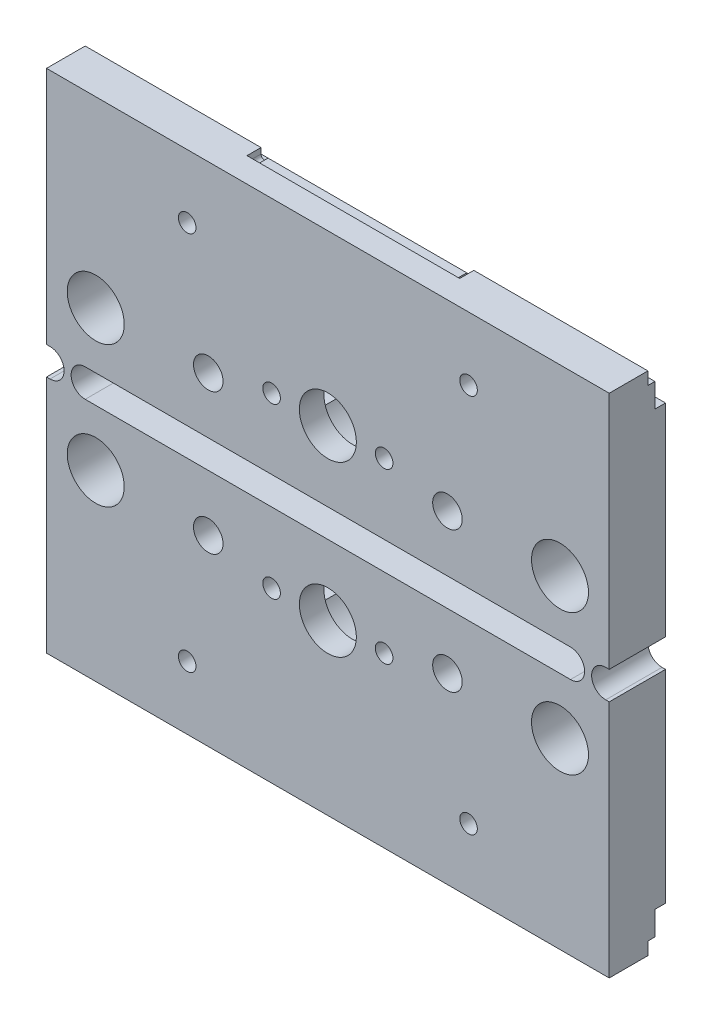
SolidWorks part; units mm, degrees
ref_plane "前视基准面" through (0, 0, 0) normal (0, 0, 1) x (1, 0, 0)
ref_plane "上视基准面" through (0, 0, 0) normal (0, 1, 0) x (1, 0, 0)
ref_plane "右视基准面" through (0, 0, 0) normal (1, 0, 0) x (0, 0, -1)
sketch "前视图草图" plane through (0, 0, 0) normal (0, 0, 1) x (1, 0, 0)
  line L0 (0, 0) -> (8.5179, 0) construction
  line L1 (0, 0) -> (0, 5.4227) construction
sketch "草图2" plane through (0, 0, 0) normal (0, 0, 1) x (1, 0, 0)
  line L0 (0, 0) -> (80, 0)
  line L1 (-200000, 0) -> (200008.5179, 0) construction
  line L2 (80, 0) -> (80, 34)
  line L3 (80, 34) -> (0, 34)
  line L4 (0, -200000) -> (0, 200005.4227) construction
  line L5 (0, 34) -> (0, 0)
  circle A0 centre (7, 8) radius 4.05
  circle A1 centre (40, 10) radius 4.05
  circle A2 centre (73, 8) radius 4.05
  dimension "D3" = 8
  dimension "D5" = 10
  dimension "D9" = 8.1
  dimension "D10" = 8.1
  dimension "D11" = 8.1
  dimension "D1" = 34
  dimension "D2" = 80
  dimension "D4" = 7
  dimension "D6" = 7
  dimension "D7" = 8
  dimension "D8" = 40
extrude "凸台-拉伸1" add sketch "草图2" along normal blind 8
sketch "草图3" plane through (0, 0, 8) normal (0, 0, 1) x (1, 0, 0)
  line L0 (16.088, 8) -> (31.4805, 8) construction
  line L1 (7, 8) -> (7, 16.8386) construction
  line L2 (73, 8) -> (73, 16.5917) construction
  line L4 (-200000, 0) -> (200008.5179, 0) construction
  circle A2 centre (23, 8) radius 2.55
  circle A3 centre (57, 8) radius 2.55
  dimension "D4" = 5.1
  dimension "D5" = 5.1
  dimension "D1" = 8
  dimension "D2" = 16
  dimension "D3" = 16
sketch "草图4" plane through (80, 0, 0) normal (1, 0, 0) x (0, 0, -1)
  line L1 (0, -200000) -> (0, 200005.4227) construction
  line L2 (-1.5, 32.2) -> (-2.5, 32.2)
  line L3 (-2.5, 32.2) -> (-2.5, 34)
  line L4 (-8, 34) -> (0, 34) construction
  line L5 (-2.5, 34) -> (0, 34)
  line L6 (-1.5, 32.2) -> (-1.5, 28.8)
  line L7 (-1.5, 28.8) -> (0, 28.8)
  line L8 (0, 28.8) -> (0, 34)
  dimension "D1" = 3.4
  dimension "D2" = 2.5
  dimension "D3" = 1.5
  dimension "D4" = 1.8
extrude "切除-拉伸2" cut sketch "草图4" against normal through all
sketch "草图5" plane through (0, 0, 8) normal (0, 0, 1) x (1, 0, 0)
  line L0 (40, 10) -> (56.5376, 10) construction
  circle A0 centre (40, 10) radius 8 construction
  circle A1 centre (48, 10) radius 1.55
  circle A2 centre (32, 10) radius 1.55
  dimension "D1" = 3.1
  dimension "D2" = 3.1
  dimension "D3" = 16
sketch "草图8" plane through (0, 0, 0) normal (0, 0, -1) x (-1, 0, 0)
  line L0 (-40, 10) -> (-57.3165, 10) construction
  line L1 (-40, 20) -> (-40, 35.6562) construction
  line L2 (-30.5, 12.85) -> (-49.5, 12.85)
  line L3 (-49.5, 7.15) -> (-30.5, 7.15)
  line L4 (200000, 0) -> (-200008.5179, 0) construction
  arc A0 (-30.5, 7.15) -> (-30.5, 12.85) centre (-30.5, 10) ccw
  arc A1 (-49.5, 12.85) -> (-49.5, 7.15) centre (-49.5, 10) ccw
  dimension "D1" = 5.7
  dimension "D2" = 9.5
  dimension "D3" = 9.5
  dimension "D4" = 10
extrude "切除-拉伸12" cut sketch "草图8" against normal blind 4.5
sketch "草图20" plane through (0, 0, 0) normal (0, 0, -1) x (-1, 0, 0)
  circle A0 centre (-40, 10) radius 6.25
  dimension "D1" = 12.5
extrude "切除-拉伸13" cut sketch "草图20" against normal blind 4.5
sketch "草图19" plane through (0, 0, 2.5) normal (0, 0, -1) x (-1, 0, 0)
  line L0 (0, 34) -> (-80, 34) construction
  line L1 (-25, 34) -> (-55.2479, 34)
  line L2 (-25, 34) -> (-25, 33.2)
  line L3 (-26, 33.2) -> (-54.2479, 33.2)
  line L4 (-55.2479, 34) -> (-55.2479, 33.2)
  line L5 (0, -200000) -> (0, 200005.4227) construction
  line L7 (0, 32.2) -> (-80, 32.2) construction
  line L8 (-56.3335, 32.7) -> (-52.9089, 32.7) construction
  line L9 (-55.2479, 1028.5823) -> (-55.2479, 33.2) construction
  line L10 (-25, 1028.5823) -> (-25, 32.7) construction
  line L11 (-55.2479, 32.7) -> (-55.2479, -973.3) construction
  line L12 (-25, 32.7) -> (-25, -973.3) construction
  arc A3 (-55.2479, 33.2) -> (-54.2479, 33.2) centre (-54.7479, 33.2) ccw
  arc A6 (-26, 33.2) -> (-25, 33.2) centre (-25.5, 33.2) ccw
  dimension "D3" = 1
  dimension "D4" = 1
  dimension "D2" = 0.8
  dimension "D1" = 0.5
  dimension "D9" = 25
extrude "切除-拉伸11" cut sketch "草图19" against normal blind 2
sketch "草图27" plane through (0, 0, 0) normal (0, 0, -1) x (-1, 0, 0)
  line L0 (-99.5618, 25) -> (-88.3386, 25) construction
  line L1 (-55.2479, 34) -> (-80, 34) construction
  line L2 (-60, 38.1181) -> (-60, 18.9205) construction
  line L3 (-20, 37.4289) -> (-20, 18.7236) construction
  line L4 (-80, 0) -> (-80, 28.8) construction
  line L5 (0, -200000) -> (0, 200005.4227) construction
  circle A0 centre (-60, 25) radius 1.55
  circle A1 centre (-20, 25) radius 1.55
  dimension "D4" = 3.1
  dimension "D5" = 3.1
  dimension "D1" = 9
  dimension "D2" = 20
  dimension "D3" = 20
hole_wizard "M5 螺纹孔1" positions "3D草图1" profile "草图25" tap size "M5" standard "GB" end condition through all
sketch3d "3D草图1"
  point P0 (57, 8, 8)
  point P3 (23, 8, 8)
sketch "草图25" plane through (57, 8, 8) normal (1, 0, 0) x (0, -1, 0)
  line L0 (0, 0) -> (0, 8)
  line L1 (0, 8) -> (2.1, 8)
  line L2 (2.1, 8) -> (2.1, 0)
  line L5 (2.1, 0) -> (0, 0)
  line L11 (0, -6.35) -> (0, 107.95) construction
  dimension "通孔螺纹孔钻头直径" = 4.2
  dimension "通孔螺纹孔钻头深度" = 8
cosmetic thread "孔螺蚊线1" parameters "D2"=5
cosmetic thread "孔螺蚊线2" parameters "D2"=5
hole_wizard "M3 螺纹孔1" positions "3D草图2" profile "草图26" tap size "M3" standard "GB" end condition through all
sketch3d "3D草图2"
  point P0 (48, 10, 8)
  point P3 (32, 10, 8)
sketch "草图26" plane through (48, 10, 8) normal (1, 0, 0) x (0, -1, 0)
  line L0 (0, 0) -> (0, 8)
  line L1 (0, 8) -> (1.25, 8)
  line L2 (1.25, 8) -> (1.25, 0)
  line L5 (1.25, 0) -> (0, 0)
  line L11 (0, -6.35) -> (0, 107.95) construction
  dimension "通孔螺纹孔钻头直径" = 2.5
  dimension "通孔螺纹孔钻头深度" = 8
cosmetic thread "孔螺蚊线3" parameters "D2"=3
cosmetic thread "孔螺蚊线4" parameters "D2"=3
hole_wizard "M3 螺纹孔2" positions "3D草图3" profile "草图28" tap size "M3" standard "GB" end condition through all
sketch3d "3D草图3"
  point P0 (60, 25, 0)
  point P3 (20, 25, 0)
sketch "草图28" plane through (60, 25, 0) normal (1, 0, 0) x (0, 1, 0)
  line L0 (0, 0) -> (0, 8)
  line L1 (0, 8) -> (1.25, 8)
  line L2 (1.25, 8) -> (1.25, 0)
  line L5 (1.25, 0) -> (0, 0)
  line L11 (0, -6.35) -> (0, 107.95) construction
  dimension "通孔螺纹孔钻头直径" = 2.5
  dimension "通孔螺纹孔钻头深度" = 8
cosmetic thread "孔螺蚊线5" parameters "D2"=3
cosmetic thread "孔螺蚊线6" parameters "D2"=3
sketch "草图22" plane through (0, 0, 8) normal (0, 0, 1) x (1, 0, 0)
  line L1 (0, -200000) -> (0, 200005.4227) construction
  line L2 (0.5, -4) -> (5.5, -4)
  line L4 (79.5, 0) -> (74.5, 0)
  line L5 (3.5, 1.9875) -> (3.5, -4.1402) construction
  line L6 (76.5, -11.5647) -> (76.5, -5.1636) construction
  line L7 (80, 0) -> (80, 34) construction
  line L8 (74.5, -4) -> (79.5, -4)
  line L9 (5.5, 0) -> (0.5, 0)
  line L10 (77.5, -2.9635) -> (77.5, -4.3032) construction
  line L11 (2.5, -8.393) -> (2.5, -15.1693) construction
  arc A0 (5.5, 0) -> (5.5, -4) centre (5.5, -2) ccw
  arc A1 (74.5, -4) -> (74.5, 0) centre (74.5, -2) ccw
  arc A2 (0.5, -4) -> (0.5, 0) centre (0.5, -2) ccw
  arc A3 (79.5, 0) -> (79.5, -4) centre (79.5, -2) ccw
  dimension "D1" = 3.5
  dimension "D2" = 3.5
  dimension "D3" = 4
  dimension "D4" = 2.5
  dimension "D5" = 2.5
extrude "凸台-拉伸2" add sketch "草图22" against normal blind 8
ref_plane "基准面1" through (0, -2, 0) normal (0, -1, 0) x (-1, 0, 0)
mirror "镜向2" about plane through (0, -2, 0) normal (0, -1, 0) of "切除-拉伸13", "切除-拉伸12", "M3 螺纹孔1", "凸台-拉伸1", "切除-拉伸2", "切除-拉伸11", "M5 螺纹孔1", "M3 螺纹孔2"
sketch "草图23" plane through (0, 0, 0) normal (0, 0, -1) x (-1, 0, 0)
  line L0 (-80, 0) -> (0, 0)
  line L1 (0, 0) -> (0, -4)
  line L2 (0, -4) -> (-80, -4)
  line L3 (-80, -4) -> (-80, 0)
sketch "草图24" plane through (0, 0, 8) normal (0, 0, 1) x (1, 0, 0)
  line L0 (80, -4) -> (80, 0)
  line L1 (80, 0) -> (0, 0)
  line L2 (0, 0) -> (0, -4)
  line L3 (0, -4) -> (80, -4)
